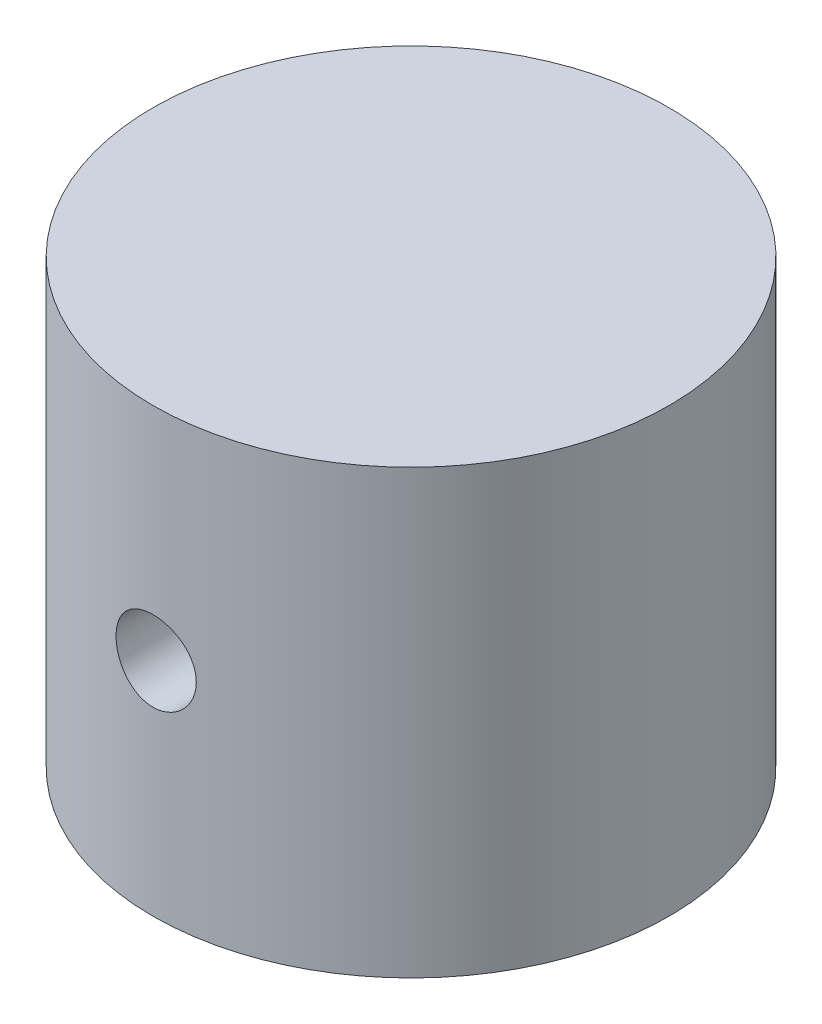
SolidWorks part; units mm, degrees
material "6061-T6 (SS)"
ref_plane "Front Plane" through (0, 0, 0) normal (0, 0, 1) x (1, 0, 0)
ref_plane "Top Plane" through (0, 0, 0) normal (0, 1, 0) x (1, 0, 0)
ref_plane "Right Plane" through (0, 0, 0) normal (1, 0, 0) x (0, 0, -1)
sketch "Sketch1" plane through (0, 0, 0) normal (0, 1, 0) x (1, 0, 0)
  circle A0 centre (0, 0) radius 11.1125
  dimension "D1" = 22.225
extrude "Boss-Extrude1" add sketch "Sketch1" along normal blind 19.05
sketch "Sketch2" plane through (0, 0, 0) normal (0, 0, 1) x (1, 0, 0)
  line L0 (-11.1125, 0) -> (11.1125, 0) construction
  circle A0 centre (0, 9.525) radius 1.7272
  dimension "D1" = 9.525
  dimension "D2" = 3.4544
extrude "Cut-Extrude1" cut sketch "Sketch2" along normal through all
